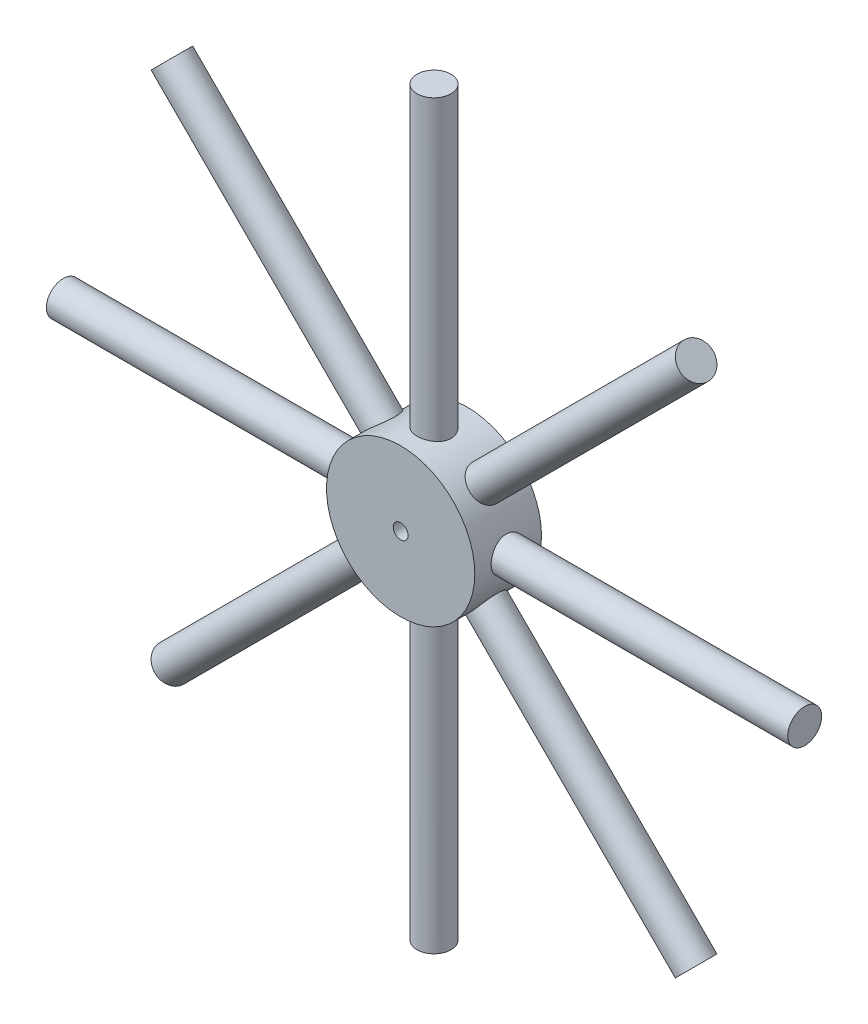
SolidWorks part; units mm, degrees
ref_plane "Plan de face" through (0, 0, 0) normal (0, 0, 1) x (1, 0, 0)
ref_plane "Plan de dessus" through (0, 0, 0) normal (0, 1, 0) x (1, 0, 0)
ref_plane "Plan de droite" through (0, 0, 0) normal (1, 0, 0) x (0, 0, -1)
sketch "Esquisse1" plane through (0, 0, 0) normal (0, 0, 1) x (1, 0, 0)
  circle A0 centre (0, 0) radius 50
  circle A1 centre (0, 0) radius 5
  dimension "D1" = 100
  dimension "D2" = 10
extrude "Boss.-Extru.1" add sketch "Esquisse1" along normal blind 45
sketch "Esquisse2" plane through (0, 0, 0) normal (0, 1, 0) x (1, 0, 0)
  line L0 (-50, -45) -> (50, -45) construction
  line L2 (0, -45) -> (0, 0) construction
  circle A0 centre (0, -22.5) radius 11.4534
  dimension "D1" = 22.9068
extrude "Boss.-Extru.2" add sketch "Esquisse2" along normal blind 250
pattern_circular "Répétition circulaire1" count 8 every 45 about axis through (0, 0, 0) along (0, 0, 1) of "Boss.-Extru.2"
